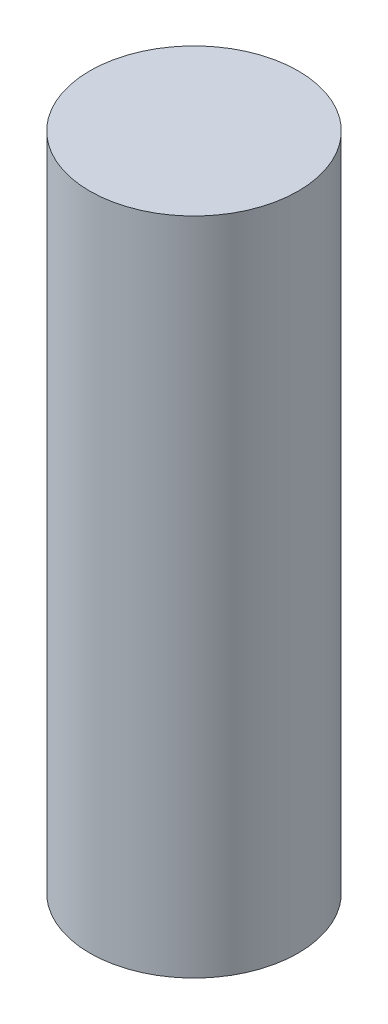
SolidWorks part; units mm, degrees
ref_plane "Front Plane" through (0, 0, 0) normal (0, 0, 1) x (1, 0, 0)
ref_plane "Top Plane" through (0, 0, 0) normal (0, 1, 0) x (1, 0, 0)
ref_plane "Right Plane" through (0, 0, 0) normal (1, 0, 0) x (0, 0, -1)
sketch "Sketch1" plane through (0, 0, 0) normal (0, 1, 0) x (1, 0, 0)
  circle A0 centre (0, 0) radius 3
extrude "Boss-Extrude1" add sketch "Sketch1" along normal blind 19
